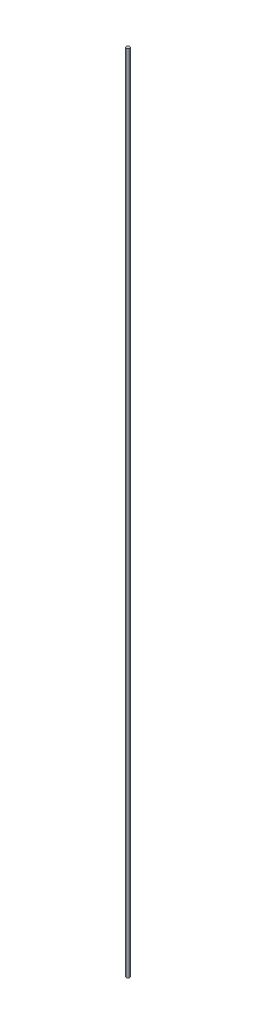
SolidWorks part; units mm, degrees
ref_plane "Front Plane" through (0, 0, 0) normal (0, 0, 1) x (1, 0, 0)
ref_plane "Top Plane" through (0, 0, 0) normal (0, 1, 0) x (1, 0, 0)
ref_plane "Right Plane" through (0, 0, 0) normal (1, 0, 0) x (0, 0, -1)
sketch "Sketch1" plane through (0, 0, 0) normal (0, 1, 0) x (1, 0, 0)
  circle A0 centre (0, 0) radius 0.762
  dimension "D1" = 1.524
extrude "Boss-Extrude1" add sketch "Sketch1" along normal blind 381
